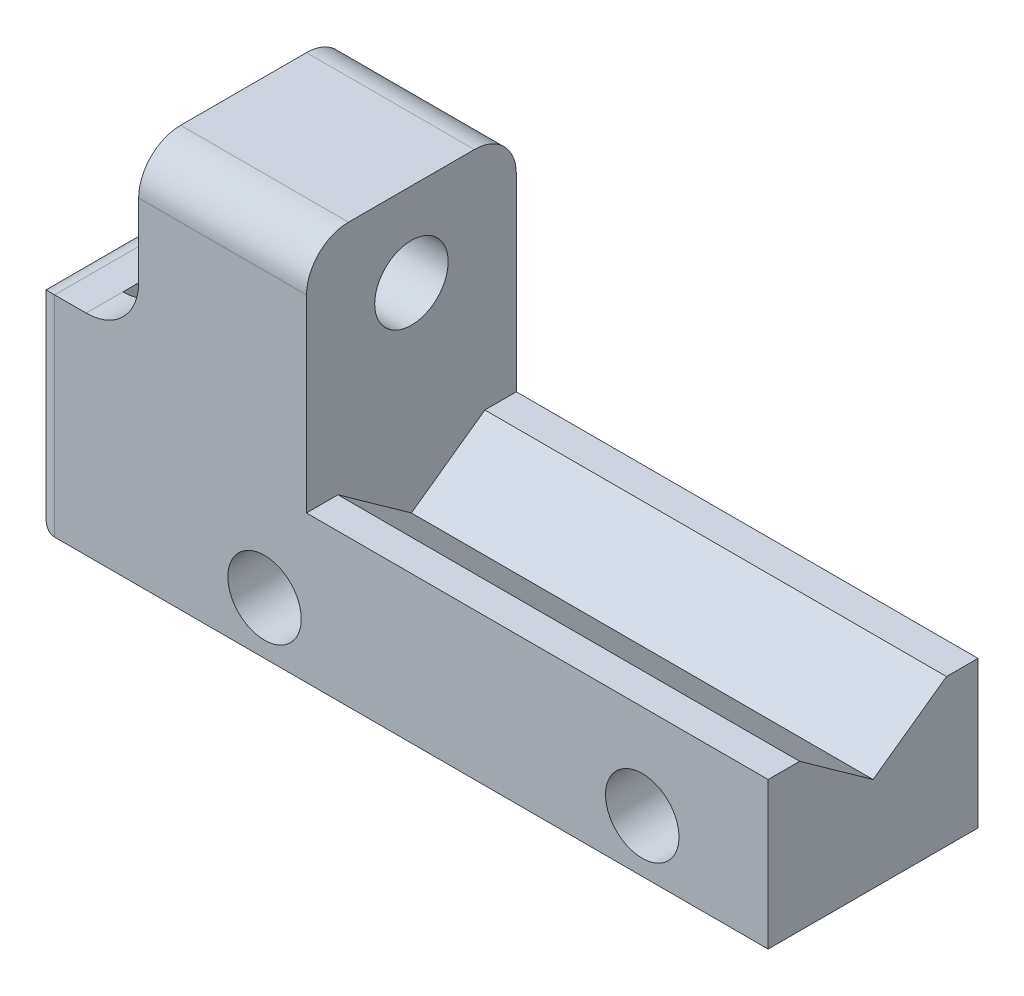
SolidWorks part; units mm, degrees
ref_plane "Спереди" through (0, 0, 0) normal (0, 0, 1) x (1, 0, 0)
ref_plane "Сверху" through (0, 0, 0) normal (0, 1, 0) x (1, 0, 0)
ref_plane "Справа" through (0, 0, 0) normal (1, 0, 0) x (0, 0, -1)
sketch "Эскиз1" plane through (0, 0, 0) normal (0, 0, 1) x (1, 0, 0)
  line L1 (-13.5, 4.5) -> (13.5, 4.5)
  line L2 (-13.5, 4.5) -> (-13.5, -4.5)
  line L3 (-13.5, -4.5) -> (13.5, -4.5)
  line L4 (13.5, 4.5) -> (13.5, -4.5)
  line L5 (-13.5, 4.5) -> (13.5, -4.5) construction
  line L6 (-13.5, -4.5) -> (13.5, 4.5) construction
  point P0 (0, 0)
  dimension "D1" = 9
  dimension "D2" = 27
extrude "Бобышка-Вытянуть1" add sketch "Эскиз1" along normal blind 10
sketch "Эскиз4" plane through (0, 4.5, 0) normal (0, 1, 0) x (1, 0, 0)
  line L0 (-13.5, 0) -> (-13.5, -10)
  line L1 (-13.5, -10) -> (-8.5, -10)
  line L2 (13.5, -10) -> (-13.5, -10) construction
  line L3 (-8.5, -10) -> (-8.5, 0)
  line L4 (13.5, 0) -> (-13.5, 0) construction
  line L5 (-8.5, 0) -> (-13.5, 0)
  dimension "D1" = 5
extrude "Бобышка-Вытянуть4" add sketch "Эскиз4" along normal blind 6
sketch "Эскиз5" plane through (0, 4.5, 0) normal (0, 1, 0) x (1, 0, 0)
  line L1 (-8.5, -10) -> (13.5, -10)
  line L2 (-8.5, -10) -> (-8.5, 0)
  line L3 (-8.5, 0) -> (13.5, 0)
  line L4 (13.5, -10) -> (13.5, 0)
extrude "Вырез-Вытянуть1" cut sketch "Эскиз5" against normal blind 2
sketch "Эскиз6" plane through (13.5, 0, 0) normal (1, 0, 0) x (0, 0, -1)
  line L0 (-10, 2.5) -> (0, 2.5) construction
  line L1 (-10, 2.5) -> (-8.5, 2.5)
  line L2 (0, 2.5) -> (-1.5, 2.5)
  line L3 (-8.5, 2.5) -> (-1.5, 2.5)
  line L6 (-8.5, 2.5) -> (-5, 0)
  line L7 (-5, 0) -> (-1.5, 2.5)
  line L8 (-1.5, 2.5) -> (-1.4554, 2.4861)
  line M4 (0, 2.5) -> (-10, 2.5)
  dimension "D1" = 1.5
extrude "Вырез-Вытянуть2" cut sketch "Эскиз6" against normal up to surface (22 mm away) contours L6 L7 M4 up to face at (-8.5, 8.5, 5)
fillet "Скругление1" radius 1 1 edges at (-11, 10.5, 10)
fillet "Скругление2" radius 1 1 edges at (-11, 10.5, 0)
sketch "Эскиз8" plane through (-13.5, 0, 0) normal (-1, 0, 0) x (0, 0, 1)
  line L0 (0, -4.5) -> (0, 15.5)
  line L1 (0, -4.5) -> (10, -4.5)
  line L2 (10, -4.5) -> (10, 15.5)
  line L3 (10, 15.5) -> (0, 15.5)
  dimension "D1" = 20
extrude "Бобышка-Вытянуть5" add sketch "Эскиз8" against normal blind 8
fillet "Скругление3" radius 2 1 edges at (-9.5, 15.5, 10)
fillet "Скругление4" radius 2 1 edges at (-9.5, 15.5, 0)
sketch "Эскиз9" plane through (13.5, 0, 0) normal (1, 0, 0) x (0, 0, -1)
  line L0 (-10, -4.5) -> (-10, 2.5)
  line L1 (-10, 2.5) -> (-8.5, 2.5)
  line L2 (-8.5, 2.5) -> (-5, 0)
  line L3 (-5, 0) -> (-1.5, 2.5)
  line L4 (-1.5, 2.5) -> (0, 2.5)
  line L5 (0, 2.5) -> (0, -4.5)
  line L6 (0, -4.5) -> (-10, -4.5)
extrude "Бобышка-Вытянуть6" add sketch "Эскиз9" along normal blind 3
sketch "Эскиз11" plane through (-5.5, 0, 0) normal (1, 0, 0) x (0, 0, -1)
  line L0 (-10, 13.5) -> (0, 13.5)
  line L1 (0, 13.5) -> (0, 15.6491)
  line L2 (0, 15.6491) -> (-10, 15.6491)
  line L3 (-10, 15.6491) -> (-10, 13.5)
extrude "Вырез-Вытянуть5" cut sketch "Эскиз11" against normal through all
fillet "Скругление5" radius 2 1 edges at (-9.5, 13.5, 10)
fillet "Скругление6" radius 2 1 edges at (-9.5, 13.5, 0)
sketch "Эскиз14" plane through (0, 0, 10) normal (0, 0, 1) x (1, 0, 0)
  line L0 (-13.5, -4.5) -> (16.5, -4.5) construction
  line L1 (-13.5, -4.5) -> (-7.5, -4.5)
  line L2 (-7.5, -4.5) -> (-7.5, -1)
  circle A0 centre (-7.5, -1) radius 1.5
  circle A1 centre (10.5, -1) radius 1.5
  dimension "D3" = 3
  dimension "D1" = 6
  dimension "D2" = 3.5
  dimension "D4" = 2
extrude "Вырез-Вытянуть6" cut sketch "Эскиз14" against normal through all
sketch "Эскиз15" plane through (0, 0, 10) normal (0, 0, 1) x (1, 0, 0)
  circle A0 centre (10.5, -1) radius 1.5
extrude "Бобышка-Вытянуть7" add sketch "Эскиз15" against normal through all
sketch "Эскиз17" plane through (0, 0, 10) normal (0, 0, 1) x (1, 0, 0)
  line L0 (-7.5, -1) -> (-7.5, -2)
  circle A0 centre (-7.5, -2) radius 1.5
  dimension "D1" = 1
sketch "Эскиз18" plane through (0, 0, 10) normal (0, 0, 1) x (1, 0, 0)
  circle A0 centre (-7.5, -1) radius 1.5
extrude "Бобышка-Вытянуть9" add sketch "Эскиз18" against normal through all
extrude "Вырез-Вытянуть7" cut sketch "Эскиз17" against normal through all
sketch "Эскиз19" plane through (0, 0, 10) normal (0, 0, 1) x (1, 0, 0)
  line L0 (-7.5, -2) -> (10.5, -2)
  circle A0 centre (10.5, -2) radius 1.5
  circle A1 centre (-7.5, -2) radius 1.5 construction
  dimension "D1" = 18
extrude "Вырез-Вытянуть8" cut sketch "Эскиз19" against normal through all contours A0
sketch "Эскиз20" plane through (16.5, 0, 0) normal (1, 0, 0) x (0, 0, -1)
  line L0 (-8.5, 2.5) -> (-5, 0)
  line L1 (-5, 0) -> (-1.5, 2.5)
  line L2 (-1.5, 2.5) -> (-8.5, 2.5)
extrude "Вырез-Вытянуть9" cut sketch "Эскиз20" against normal up to surface (22 mm away) up to face at (-5.5, 6.7587, 5)
sketch "Эскиз23" plane through (-13.5, 0, 0) normal (-1, 0, 0) x (0, 0, 1)
  line L0 (10, 11.5) -> (10, -4.5) construction
  line L1 (0, -4.5) -> (10, -4.5)
  line L2 (0, -4.5) -> (0, 5.5)
  line L3 (0, 5.5) -> (10, 5.5)
  line L4 (10, -4.5) -> (10, 5.5)
  dimension "D1" = 10
extrude "Бобышка-Вытянуть10" add sketch "Эскиз23" along normal blind 5
sketch "Эскиз24" plane through (-18.5, 0, 0) normal (-1, 0, 0) x (0, 0, 1)
  line L0 (5, -4.5) -> (5, 5.5)
  line L1 (0, -4.5) -> (10, -4.5) construction
  line L2 (10, 5.5) -> (0, 5.5) construction
  line L3 (-0.6593, 0.5) -> (11.8767, 0.5) construction
  line L4 (5, 5.5) -> (5, 0.5)
  line L5 (5, 0.5) -> (1.75, 0.5)
  line L6 (1.75, 0.5) -> (1.75, 1.75)
  line L7 (1.75, 1.75) -> (8.25, 1.75)
  line L8 (8.25, 1.75) -> (8.25, -0.75)
  line L9 (8.25, -0.75) -> (1.75, -0.75)
  line L10 (1.75, -0.75) -> (1.75, 0.5)
  point P14 (5, 1.75)
  dimension "D1" = 2.5
  dimension "D2" = 5
  dimension "D3" = 6.5
extrude "Вырез-Вытянуть11" cut sketch "Эскиз24" against normal blind 4 contours L7 L6 L5 L0 | L0 L3 L8 L7 | L10 L9 L0 L5 | L3 L0 L9 L8
sketch "Эскиз25" plane through (0, 5.5, 0) normal (0, 1, 0) x (1, 0, 0)
  line L0 (-13.5, -5) -> (-13.5, -1.75)
  line L1 (-13.5, -8) -> (-13.5, -2) construction
  line L2 (-13.5, -10) -> (-13.5, 0) construction
  line L3 (-13.5, -1.75) -> (-16, -1.75)
  line L4 (-16, -1.75) -> (-16, -8.25)
  line L5 (-13.5, -5) -> (-13.5, -8.25)
  line L6 (-13.5, -8.25) -> (-16, -8.25)
  dimension "D1" = 6.5
  dimension "D2" = 6.5
  dimension "D3" = 2.5
extrude "Вырез-Вытянуть12" cut sketch "Эскиз25" against normal blind 6.25
fillet "Скругление7" radius 2.5 2 edges
fillet "Скругление8" radius 1 4 edges at (-18.5, 0.5, 0) (-18.5, -4.5, 5) (-18.5, 0.5, 10) (-18.5, 5.5, 5)
sketch "Эскиз26" plane through (-13.5, 0, 0) normal (-1, 0, 0) x (0, 0, 1)
  line L0 (5, -4.5) -> (5, 9.5)
  line L1 (10, -4.5) -> (0, -4.5) construction
  circle A0 centre (5, 9.5) radius 1.5
  dimension "D2" = 3
  dimension "D1" = 14
extrude "Вырез-Вытянуть13" cut sketch "Эскиз26" against normal through all
sketch "Эскиз27" plane through (0, 0, 0) normal (0, 0, -1) x (-1, 0, 0)
  circle A1 centre (-10.5, -2) radius 1.75
  circle A2 centre (7.5, -2) radius 1.75
  dimension "D1" = 3.5
  dimension "D2" = 3.5
extrude "Вырез-Вытянуть14" cut sketch "Эскиз27" against normal through all
sketch "Эскиз28" plane through (-13.5, 0, 0) normal (-1, 0, 0) x (0, 0, 1)
  circle A0 centre (5, 9.5) radius 1.75
  dimension "D1" = 3.5
extrude "Вырез-Вытянуть15" cut sketch "Эскиз28" against normal through all
